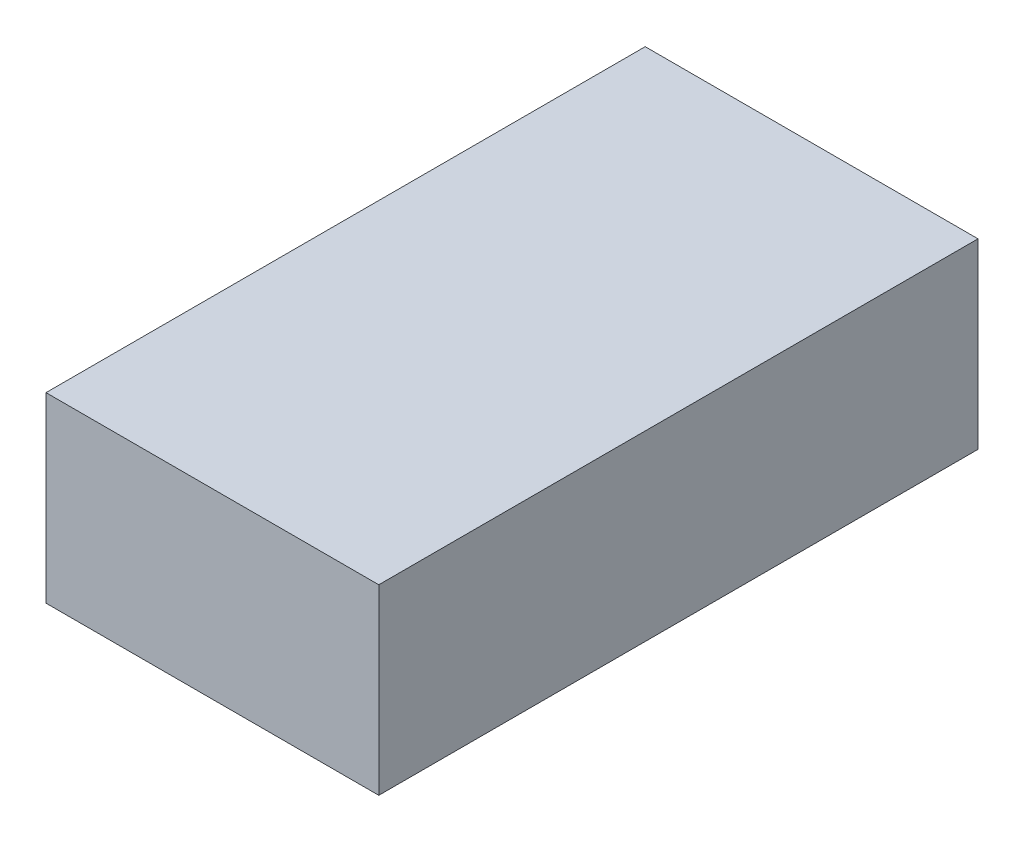
SolidWorks part; units mm, degrees
ref_plane "Front Plane" through (0, 0, 0) normal (0, 0, 1) x (1, 0, 0)
ref_plane "Top Plane" through (0, 0, 0) normal (0, 1, 0) x (1, 0, 0)
ref_plane "Right Plane" through (0, 0, 0) normal (1, 0, 0) x (0, 0, -1)
sketch "CurveSketch" plane through (0, 0, 0) normal (0, 0, 1) x (1, 0, 0)
  line L0 (-20.0525, -1.8635) -> (11.6665, -1.8635)
  line L1 (11.6665, -1.8635) -> (11.6665, 15.5175)
  line L2 (11.6665, 15.5175) -> (-20.0525, 15.5175)
  line L3 (-20.0525, 15.5175) -> (-20.0525, -1.8635)
extrude "CurveBoss" add sketch "CurveSketch" along normal mid plane 57.113
